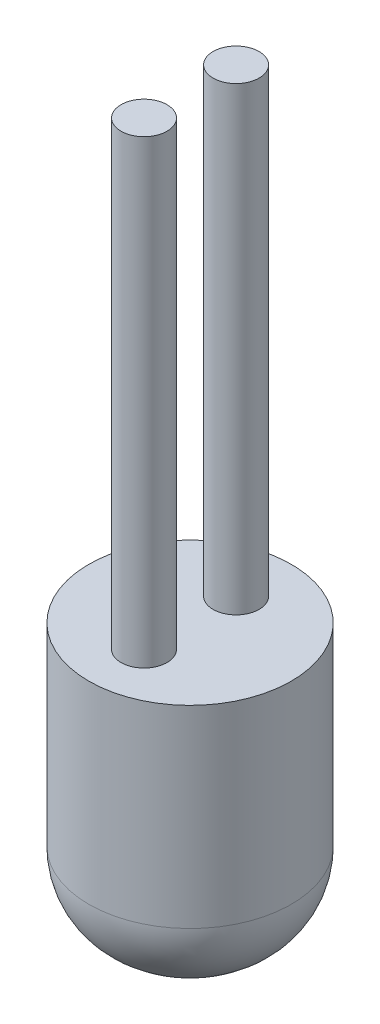
SolidWorks part; units mm, degrees
ref_plane "前视基准面" through (0, 0, 0) normal (0, 0, 1) x (1, 0, 0)
ref_plane "上视基准面" through (0, 0, 0) normal (0, 1, 0) x (1, 0, 0)
ref_plane "右视基准面" through (0, 0, 0) normal (1, 0, 0) x (0, 0, -1)
sketch "草图1" plane through (0, 0, 0) normal (0, 1, 0) x (1, 0, 0)
  circle A0 centre (0, 0) radius 1.1
  dimension "D1" = 2.2
extrude "拉伸1" add sketch "草图1" along normal blind 3
fillet "圆角1" radius 0.9 1 edges at (0, 0, 1.1)
sketch "草图2" plane through (0, 3, 0) normal (0, 1, 0) x (-1, 0, 0)
  line L0 (0, -1.2054) -> (0, 1.2256) construction
  line L1 (-1.1771, 0) -> (1.2297, 0) construction
  circle A0 centre (0, -0.5) radius 0.25
  circle A1 centre (0, 0.5) radius 0.25
  dimension "D1" = 0.5
  dimension "D2" = 1
extrude "拉伸2" add sketch "草图2" along normal blind 5
